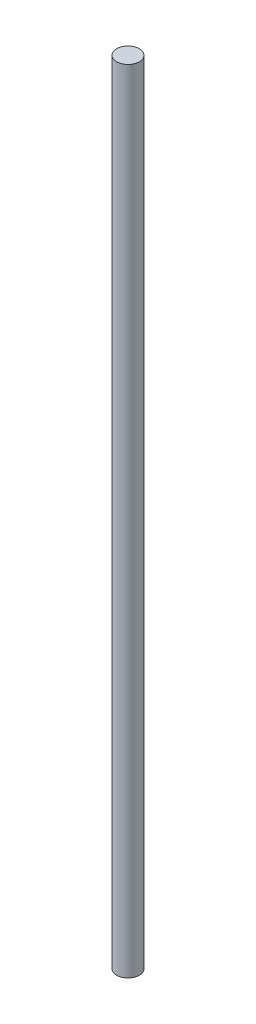
SolidWorks part; units mm, degrees
ref_plane "Front Plane" through (0, 0, 0) normal (0, 0, 1) x (1, 0, 0)
ref_plane "Top Plane" through (0, 0, 0) normal (0, 1, 0) x (1, 0, 0)
ref_plane "Right Plane" through (0, 0, 0) normal (1, 0, 0) x (0, 0, -1)
sketch "Sketch1" plane through (0, 0, 0) normal (0, 1, 0) x (1, 0, 0)
  circle A0 centre (0, 0) radius 2
  dimension "D1" = 4
extrude "Boss-Extrude1" add sketch "Sketch1" along normal blind 140
